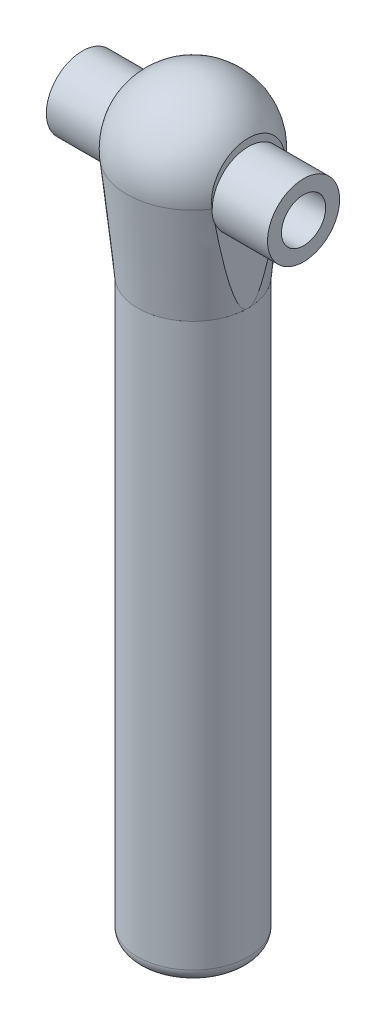
SolidWorks part; units mm, degrees
material "ABS"
ref_plane "Płaszczyzna przednia" through (0, 0, 0) normal (0, 0, 1) x (1, 0, 0)
ref_plane "Płaszczyzna górna" through (0, 0, 0) normal (0, 1, 0) x (1, 0, 0)
ref_plane "Płaszczyzna prawa" through (0, 0, 0) normal (1, 0, 0) x (0, 0, -1)
sketch "Szkic1" plane through (0, 0, 0) normal (0, 1, 0) x (1, 0, 0)
  circle A0 centre (0, 0) radius 12.5
  dimension "D1" = 25
extrude "Dodanie-wyciągnięcie1" add sketch "Szkic1" along normal blind 130
sketch "Szkic2" plane through (0, 0, 0) normal (1, 0, 0) x (0, 0, -1)
  line L0 (12.5, 130) -> (-12.5, 130) construction
  line L1 (12.5, 130) -> (14.9208, 153.4604)
  line L2 (0, 182.1231) -> (0, 51.4234) construction
  line L4 (0, 170) -> (0, 140)
  line L5 (12.5, 130) -> (0, 130)
  line L6 (0, 130) -> (0, 140)
  arc A1 (0, 170) -> (0, 140) centre (0, 155) cw
  dimension "D1" = 15
  dimension "D2" = 25
revolve "Obrót1" add sketch "Szkic2" angle 360 about L2
sketch "Szkic3" plane through (0, 0, 0) normal (0, -1, 0) x (1, 0, 0)
  line L0 (0, 25.9244) -> (0, -25.062) construction
  line L1 (-12.5, 15) -> (-17.5, 15)
  line L2 (-12.5, 15) -> (-12.5, -15)
  line L3 (-12.5, -15) -> (-17.5, -15)
  line L4 (-17.5, 15) -> (-17.5, -15)
  line L5 (12.5, -15) -> (17.5, -15)
  line L6 (17.5, 15) -> (17.5, -15)
  line L7 (12.5, 15) -> (17.5, 15)
  line L8 (12.5, 15) -> (12.5, -15)
  circle A0 centre (0, 0) radius 12.5 construction
  point P4 (-17.5, 0)
  dimension "D1" = 30
  dimension "D2" = 5
extrude "Wytnij-wyciągnięcie1" cut sketch "Szkic3" against normal through all
sketch "Szkic4" plane through (12.5, 0, 0) normal (1, 0, 0) x (0, 0, -1)
  line L0 (-14.9208, 153.4604) -> (-8.1474, 153.4604) construction
  circle A0 centre (0, 153.4604) radius 5
  point P2 (0, 0)
  point P5 (0, 153.4604)
  point P6 (0, 0)
  dimension "D1" = 10
extrude "Wytnij-wyciągnięcie2" cut sketch "Szkic4" against normal through all
sketch "Szkic5" plane through (0, 0, 0) normal (0, -1, 0) x (1, 0, 0)
  circle A0 centre (0, 0) radius 5
  dimension "D1" = 10
extrude "Wytnij-wyciągnięcie3" cut sketch "Szkic5" against normal blind 130
fillet "Zaokrąglenie1" radius 3 2 edges at (0, 0, 12.5) (0, 0, -5)
sketch "Szkic6" plane through (0, 0, 0) normal (1, 0, 0) x (0, 0, -1)
  circle A0 centre (0, 153.4604) radius 8.1474
  circle A1 centre (0, 153.4604) radius 5
  circle A2 centre (0, 153.4604) radius 5 construction
extrude "Dodanie-wyciągnięcie2" add sketch "Szkic6" along normal blind 25 and the other way blind 25
